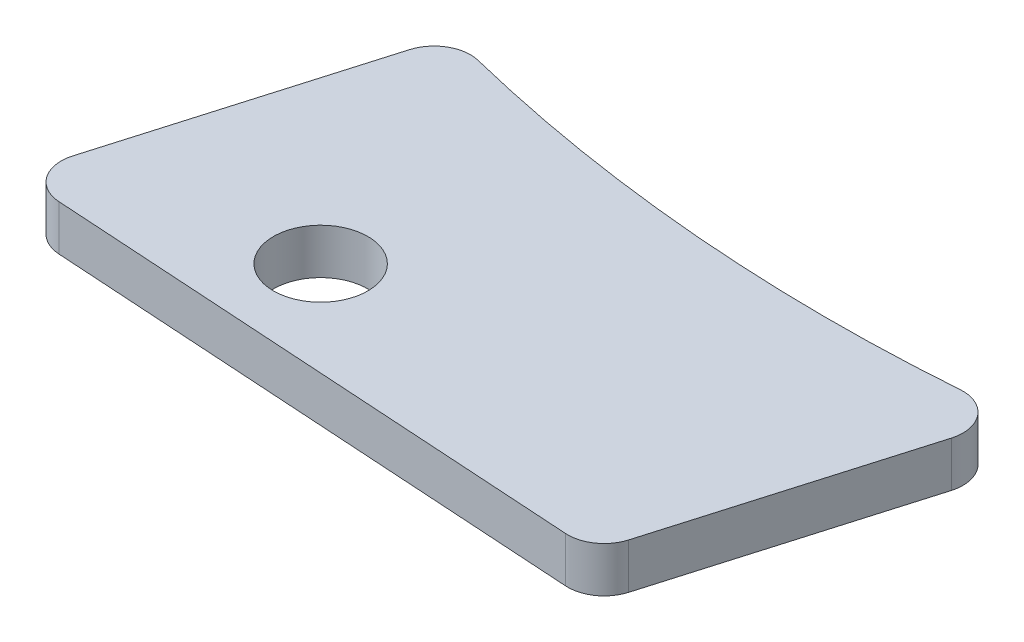
SolidWorks part; units mm, degrees
material "6061-T6 (SS)"
ref_plane "X-Y Datum" through (0, 0, 0) normal (0, 0, 1) x (1, 0, 0)
ref_plane "X-Z Datum" through (0, 0, 0) normal (0, 1, 0) x (1, 0, 0)
ref_plane "Y-Z Datum" through (0, 0, 0) normal (1, 0, 0) x (0, 0, -1)
sketch "Sketch1" plane through (0, 0, 0) normal (0, 1, 0) x (1, 0, 0)
  line L0 (-48.709, -102.9854) -> (-49.6021, -106.0322)
  line L1 (-48.8134, -119.2164) -> (-53.5341, -139.1464) construction
  line L2 (-29.9586, -141.8647) -> (-30.0199, -121.3833) construction
  line L3 (-49.6021, -106.0322) -> (-55.632, -126.6031)
  line L4 (-5.8847, -106.3423) -> (-6.8909, -109.7752)
  line L5 (-6.8909, -109.7752) -> (-12.6182, -129.3139)
  line L6 (-12.6182, -129.3139) -> (-55.632, -126.6031)
  arc A0 (-49.6021, -106.0322) -> (-128.552, -36.8555) centre (-17.9362, 9.7477) ccw construction
  arc A1 (-48.709, -102.9854) -> (-125.892, -35.5498) centre (-18.3348, 9.6665) ccw construction
  circle A2 centre (-39.5446, -121.4118) radius 3.3
  arc A3 (-31.4516, -142.2427) -> (-52.1663, -139.8543) centre (-42.6396, -148.2526) ccw construction
  arc A4 (-53.5341, -139.1464) -> (-52.1663, -139.8543) centre (-52.7617, -139.3294) ccw construction
  arc A5 (-30.0199, -121.3833) -> (-48.8134, -119.2164) centre (-39.5448, -121.4118) ccw construction
  arc A6 (-31.4516, -142.2427) -> (-29.9586, -141.8647) centre (-30.7524, -141.8671) ccw construction
  arc A7 (-49.6021, -106.0322) -> (8.2407, -107.3954) centre (-17.9362, 9.7477) ccw construction
  arc A8 (-48.709, -102.9854) -> (-5.8847, -106.3423) centre (-18.3348, 9.6665) ccw
  point P21 (-55.5098, -126.1862)
  point P26 (-21.3562, -129.3139)
  point P27 (-55.6896, -126.7998)
  point P29 (-15.7971, -129.3139)
  dimension "D1" = 6.6
  dimension "D2" = 12.7
  dimension "D3" = 0.7938
  dimension "D4" = 9.525
  dimension "D13" = 116.675
  dimension "D5" = 29.9586
  dimension "D6" = 30.0199
  dimension "D7" = 42.6396
  dimension "D8" = 102.9854
  dimension "D9" = 39.5446
  dimension "D10" = 106.0322
  dimension "D11" = 119.2164
  dimension "D12" = 48.709
  dimension "D14" = 49.6021
  dimension "D16" = 7.9021
extrude "Boss-Extrude1" add sketch "Sketch1" along normal blind 3.175
fillet "Fillet1" radius 2.54 4 edges at (-5.8847, 1.5875, 106.3423) (-48.709, 1.5875, 102.9854) (-12.6182, 1.5875, 129.3139) (-55.632, 1.5875, 126.6031)
